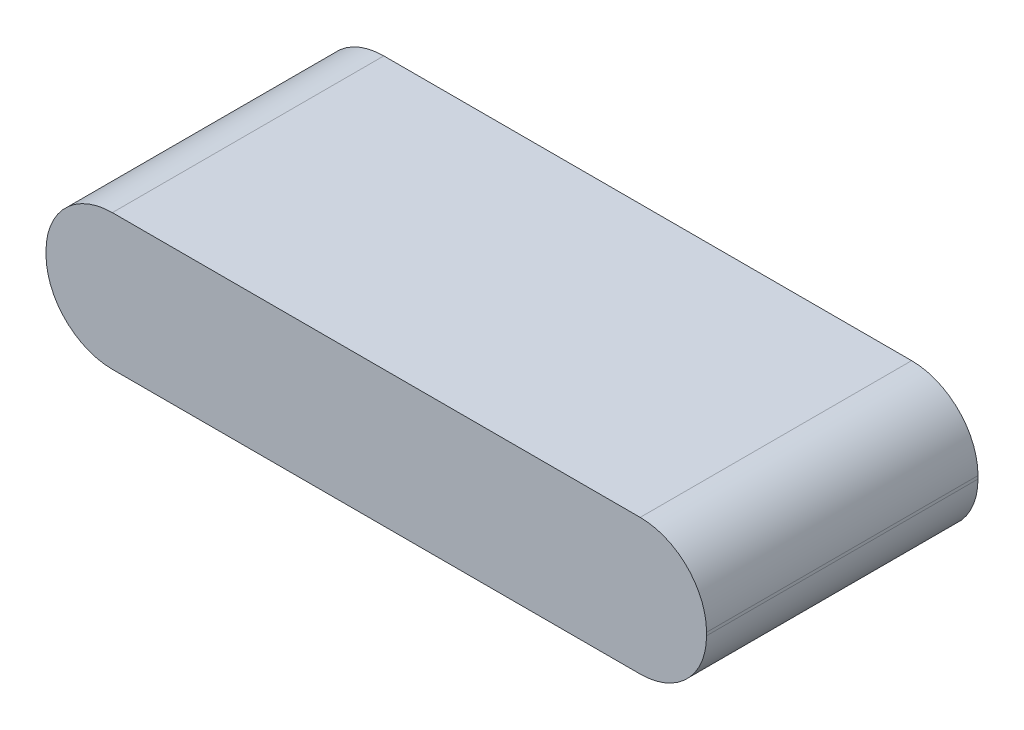
SolidWorks part; units mm, degrees
ref_plane "Front Plane" through (0, 0, 0) normal (0, 0, 1) x (1, 0, 0)
ref_plane "Top Plane" through (0, 0, 0) normal (0, 1, 0) x (1, 0, 0)
ref_plane "Right Plane" through (0, 0, 0) normal (1, 0, 0) x (0, 0, -1)
sketch "Sketch1" plane through (0, 0, 0) normal (0, 1, 0) x (1, 0, 0)
  line L1 (0, 0) -> (111.252, 0)
  line L2 (0, 0) -> (0, 45.72)
  line L3 (0, 45.72) -> (111.252, 45.72)
  line L4 (111.252, 0) -> (111.252, 45.72)
  dimension "D1" = 111.252
  dimension "D2" = 45.72
extrude "Boss-Extrude1" add sketch "Sketch1" along normal blind 22.86
fillet "Fillet1" radius 11.176 4 edges at (111.252, 0, -22.86) (111.252, 22.86, -22.86) (0, 0, -22.86) (0, 22.86, -22.86)
